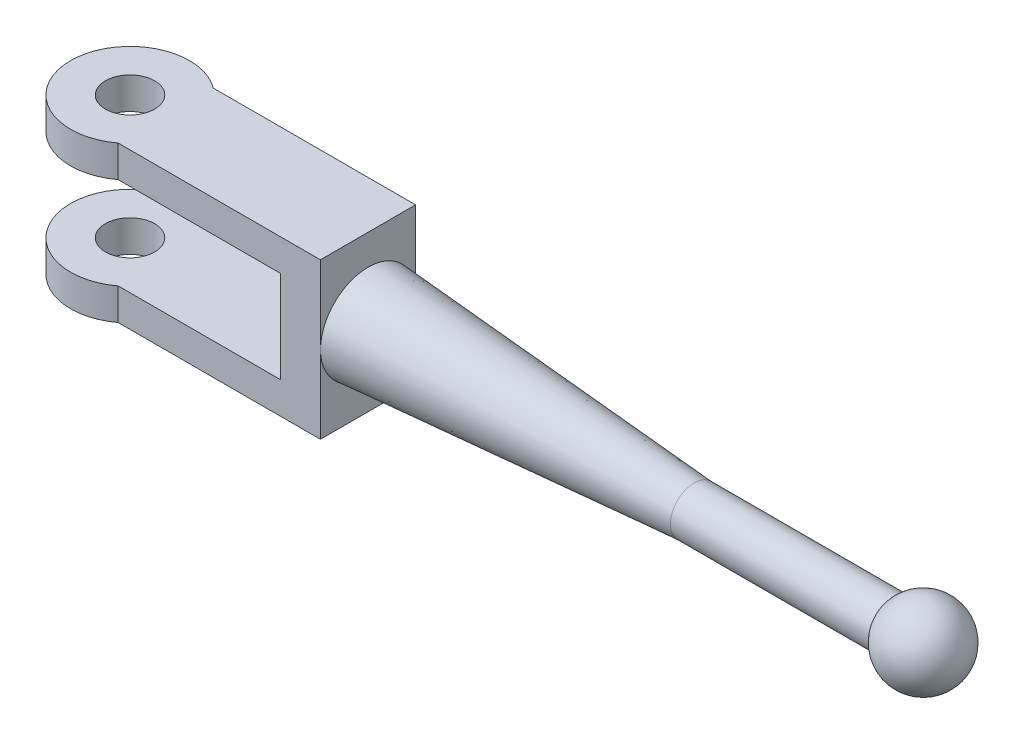
SolidWorks part; units mm, degrees
ref_plane "前视基准面" through (0, 0, 0) normal (0, 0, 1) x (1, 0, 0)
ref_plane "上视基准面" through (0, 0, 0) normal (0, 1, 0) x (1, 0, 0)
ref_plane "右视基准面" through (0, 0, 0) normal (1, 0, 0) x (0, 0, -1)
sketch "草图1" plane through (0, 0, 0) normal (0, 1, 0) x (1, 0, 0)
  line L0 (0, 6) -> (30, 6)
  line L1 (30, 6) -> (30, -6)
  line L2 (30, -6) -> (0, -6)
  circle A0 centre (0, 0) radius 3.1
  arc A1 (0, 6) -> (0, -6) centre (0, 0) ccw
  dimension "D1" = 6.2
  dimension "D2" = 6
  dimension "D3" = 30
extrude "凸台-拉伸1" add sketch "草图1" along normal blind 4
ref_plane "基准面1" through (0, 15.6, 0) normal (0, 1, 0) x (1, 0, 0)
sketch "草图2" plane through (0, 15.6, 0) normal (0, 1, 0) x (1, 0, 0)
  line L3 (0, -6) -> (30, -6)
  line L4 (30, -6) -> (30, 6)
  line L5 (30, 6) -> (0, 6)
  line L6 (0, -6) -> (30, -6)
  line L7 (30, -6) -> (30, 6)
  line L8 (30, 6) -> (0, 6)
  circle A0 centre (0, 0) radius 3.1 construction
  arc A1 (0, 6) -> (0, -6) centre (0, 0) ccw
  arc A2 (0, 6) -> (0, -6) centre (0, 0) ccw
  circle A3 centre (0, 0) radius 3.1
  dimension "D1" = 0
extrude "凸台-拉伸2" add sketch "草图2" along normal blind 4 separate body
sketch "草图3" plane through (30, 0, 0) normal (1, 0, 0) x (0, 0, -1)
  line L1 (-6, 19.6) -> (6, 19.6)
  line L2 (-6, 19.6) -> (-6, 0)
  line L3 (-6, 0) -> (6, 0)
  line L4 (6, 19.6) -> (6, 0)
extrude "凸台-拉伸3" add sketch "草图3" against normal blind 5
sketch "草图4" plane through (0, 19.6, 0) normal (0, 1, 0) x (1, 0, 0)
  circle A0 centre (0, 0) radius 3.1
  circle A1 centre (0, 0) radius 7.5
  dimension "D1" = 15
extrude "凸台-拉伸4" add sketch "草图4" against normal blind 4
sketch "草图5" plane through (0, 0, 0) normal (0, -1, 0) x (1, 0, 0)
  circle A0 centre (0, 0) radius 3.1
  circle A1 centre (0, 0) radius 7.5
extrude "凸台-拉伸5" add sketch "草图5" against normal blind 4
sketch "草图7" plane through (0, 0, 0) normal (0, 0, 1) x (1, 0, 0)
  line L0 (30, 9.8) -> (100, 9.8) construction
  line L1 (30, 19.6) -> (30, 0) construction
  line L2 (96.1257, 12.8) -> (71.1257, 12.8)
  line L3 (0, 0) -> (0, 19.6) construction
  line L4 (30.0125, 15.8) -> (71.1257, 12.8)
  line L6 (4.5, 19.6) -> (-7.5, 19.6) construction
  line L9 (100, 9.8) -> (104.9, 9.8) construction
  line L10 (30, 9.8) -> (104.9, 9.8)
  line L11 (30.0125, 15.8) -> (30, 9.8)
  arc A0 (104.9, 9.8) -> (95.1, 9.8) centre (100, 9.8) ccw construction
  arc A1 (104.9, 9.8) -> (96.1257, 12.8) centre (100, 9.8) ccw
  dimension "D2" = 4.9
  dimension "D1" = 100
  dimension "D3" = 3
  dimension "D4" = 6
  dimension "D5" = 25
revolve "旋转1" add sketch "草图7" angle 360 about L10
